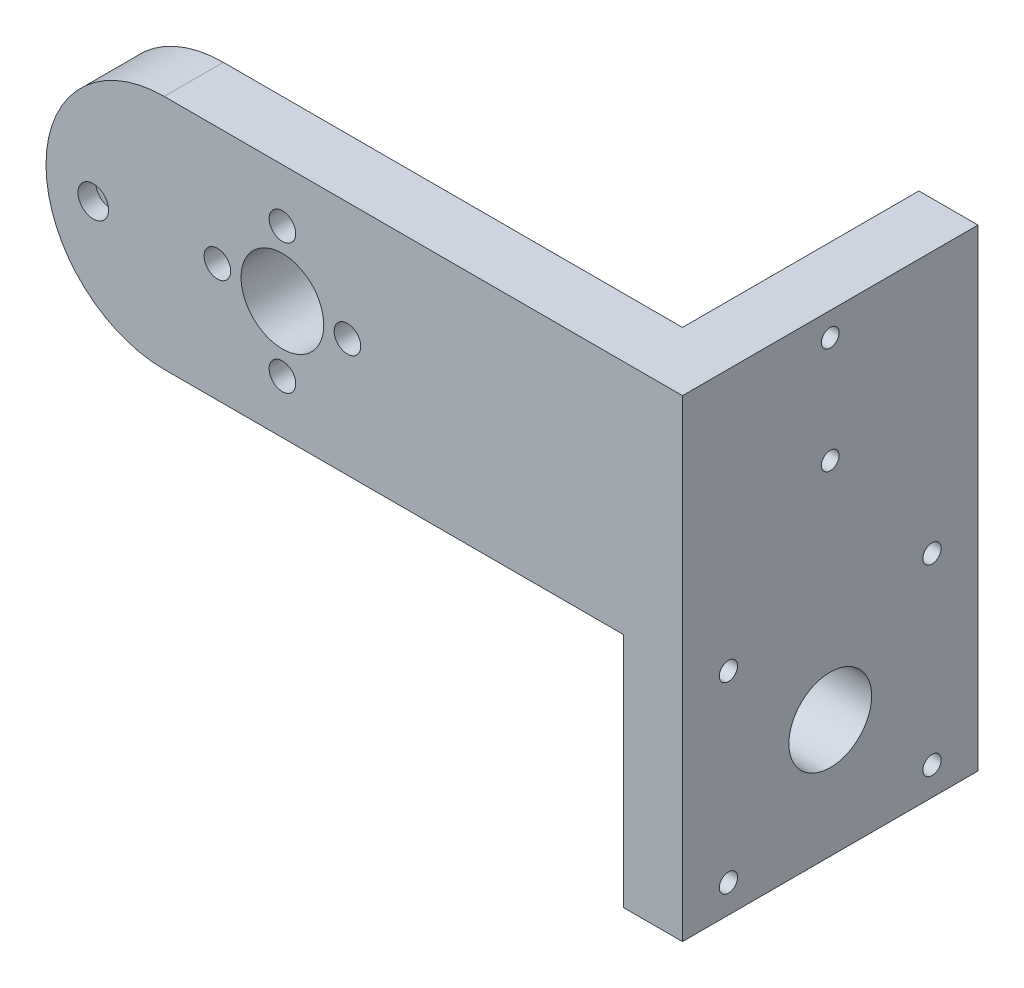
SolidWorks part; units mm, degrees
material "PLA+"
ref_plane "Front Plane" through (0, 0, 0) normal (0, 0, 1) x (1, 0, 0)
ref_plane "Top Plane" through (0, 0, 0) normal (0, 1, 0) x (1, 0, 0)
ref_plane "Right Plane" through (0, 0, 0) normal (1, 0, 0) x (0, 0, -1)
sketch "Sketch3" plane through (0, 0, 0) normal (0, 0, 1) x (1, 0, 0)
  line L0 (0, 20) -> (87.69, 20)
  line L1 (0, -20) -> (87.69, -20)
  line L2 (87.69, 20) -> (87.69, -20)
  arc A1 (0, 20) -> (0, -20) centre (0, 0) ccw
  dimension "D1" = 87.69
  dimension "D2" = 40
extrude "Boss-Extrude1" add sketch "Sketch3" along normal mid plane 10
sketch "Sketch6" plane through (0, 0, 5) normal (0, 0, 1) x (1, 0, 0)
  line L0 (20, 11) -> (20, -11) construction
  line L1 (9, 0) -> (31, 0) construction
  line L2 (87.69, 0) -> (20, 0) construction
  line L3 (87.69, -20) -> (87.69, 20) construction
  circle A0 centre (20, 0) radius 7
  circle A1 centre (20, 0) radius 11 construction
  circle A2 centre (20, 11) radius 2.25
  circle A3 centre (31, 0) radius 2.25
  circle A4 centre (20, -11) radius 2.25
  circle A5 centre (9, 0) radius 2.25
  arc A6 (0, 20) -> (0, -20) centre (0, 0) ccw construction
  point P17 (-20, 0)
  dimension "D1" = 14
  dimension "D2" = 22
  dimension "D3" = 4.5
  dimension "D4" = 4.5
  dimension "D5" = 4.5
  dimension "D6" = 4.5
  dimension "D7" = 67.69
  dimension "D8" = 40
extrude "Cut-Extrude1" cut sketch "Sketch6" against normal through all
sketch "Sketch9" plane through (87.69, 0, 0) normal (1, 0, 0) x (0, 0, -1)
  line L0 (5, 20) -> (45, 20)
  line L1 (5, -20) -> (45, -20)
  line L2 (45, 20) -> (45, -20)
  line L7 (5, -20) -> (5, 20)
  line L8 (5, 20) -> (-5, 20)
  line L9 (-5, 20) -> (-5, -20)
  line L10 (-5, -20) -> (5, -20)
  line L12 (5, 20) -> (-5, 20)
  line L13 (-5, 20) -> (-5, -20)
  line L14 (-5, -20) -> (5, -20)
  dimension "D1" = 40
  dimension "D2" = 0
extrude "Boss-Extrude2" add sketch "Sketch9" against normal blind 10
sketch "Sketch11" plane through (0, 0, 5) normal (0, 0, 1) x (1, 0, 0)
  line L0 (0, 0) -> (0, -1.375) construction
  line L1 (0, -1.375) -> (-12, -1.375) construction
  circle A0 centre (-12, -1.375) radius 2.59
  dimension "D2" = 5.18
  dimension "D1" = 1.375
  dimension "D3" = 12
extrude "Cut-Extrude3" cut sketch "Sketch11" against normal blind 3
sketch "Sketch16" plane through (87.69, 0, 0) normal (1, 0, 0) x (0, 0, -1)
  line L0 (-5, 0) -> (45, 0) construction
  line L1 (-5, -20) -> (-5, 20) construction
  line L2 (45, -20) -> (45, 20) construction
  line L3 (20, 0) -> (20, 20) construction
  line L4 (-5, 20) -> (45, 20) construction
  line L5 (20, 0) -> (20, -20) construction
  line L6 (-5, -20) -> (45, -20) construction
  circle A0 centre (20, 16) radius 1.5
  circle A1 centre (20, -2) radius 1.5
  dimension "D2" = 3
  dimension "D3" = 3
  dimension "D1" = 4
  dimension "D4" = 18
extrude "Cut-Extrude6" cut sketch "Sketch16" against normal through all
sketch "Sketch24" plane through (0, -20, 0) normal (0, -1, 0) x (-1, 0, 0)
  line L1 (-87.69, -5) -> (-77.69, -5)
  line L2 (-87.69, -5) -> (-87.69, 45)
  line L3 (-87.69, 45) -> (-77.69, 45)
  line L4 (-77.69, -5) -> (-77.69, 45)
extrude "Boss-Extrude8" add sketch "Sketch24" along normal blind 40
sketch "Sketch25" plane through (87.69, 0, 0) normal (1, 0, 0) x (0, 0, -1)
  line L0 (-5, -20) -> (45, -20) construction
  line L1 (-5, -60) -> (-5, 20) construction
  line L2 (45, -60) -> (45, 20) construction
  line L3 (20, -20) -> (20, -60) construction
  line L4 (45, -60) -> (-5, -60) construction
  circle A0 centre (20, -40) radius 7
  dimension "D1" = 14
extrude "Cut-Extrude10" cut sketch "Sketch25" against normal through all
sketch "Sketch26" plane through (87.69, 0, 0) normal (1, 0, 0) x (0, 0, -1)
  line L0 (-5, -20) -> (45, -20) construction
  line L1 (-5, -60) -> (-5, 20) construction
  line L2 (45, -60) -> (45, 20) construction
  line L3 (-5, -39.7235) -> (45, -39.7235) construction
  line L5 (2.78, -55.2235) -> (37.22, -55.2235)
  line L6 (2.78, -55.2235) -> (2.78, -24.2235)
  line L7 (2.78, -24.2235) -> (37.22, -24.2235)
  line L8 (37.22, -55.2235) -> (37.22, -24.2235)
  line L9 (2.78, -55.2235) -> (37.22, -24.2235) construction
  line L10 (2.78, -24.2235) -> (37.22, -55.2235) construction
  circle A0 centre (2.78, -24.2235) radius 1.55
  circle A1 centre (37.22, -24.2235) radius 1.55
  circle A2 centre (37.22, -55.2235) radius 1.55
  circle A3 centre (2.78, -55.2235) radius 1.55
  point P8 (20, -39.7235)
  dimension "D4" = 3.1
  dimension "D5" = 3.1
  dimension "D6" = 3.1
  dimension "D7" = 3.1
  dimension "D1" = 34.44
  dimension "D2" = 31
  dimension "D3" = 4.2235
extrude "Cut-Extrude11" cut sketch "Sketch26" against normal through all contours A0 | A1 | A2 | A3
